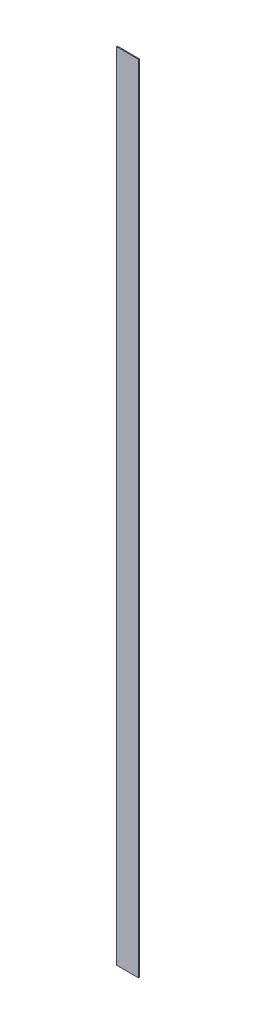
SolidWorks part; units mm, degrees
ref_plane "Спереди" through (0, 0, 0) normal (0, 0, 1) x (1, 0, 0)
ref_plane "Сверху" through (0, 0, 0) normal (0, 1, 0) x (1, 0, 0)
ref_plane "Справа" through (0, 0, 0) normal (1, 0, 0) x (0, 0, -1)
other "Гор"
sketch "Эскиз1" plane through (0, 0, 0) normal (0, 0, 1) x (1, 0, 0)
  line L1 (-25, 890) -> (25, 890)
  line L2 (-25, 890) -> (-25, -890)
  line L3 (-25, -890) -> (25, -890)
  line L4 (25, 890) -> (25, -890)
  line L5 (-25, 890) -> (25, -890) construction
  line L6 (-25, -890) -> (25, 890) construction
  point P0 (0, 0)
  dimension "D1" = 50
  dimension "D2" = 1780
extrude "Бобышка-Вытянуть1" add sketch "Эскиз1" along normal mid plane 2
